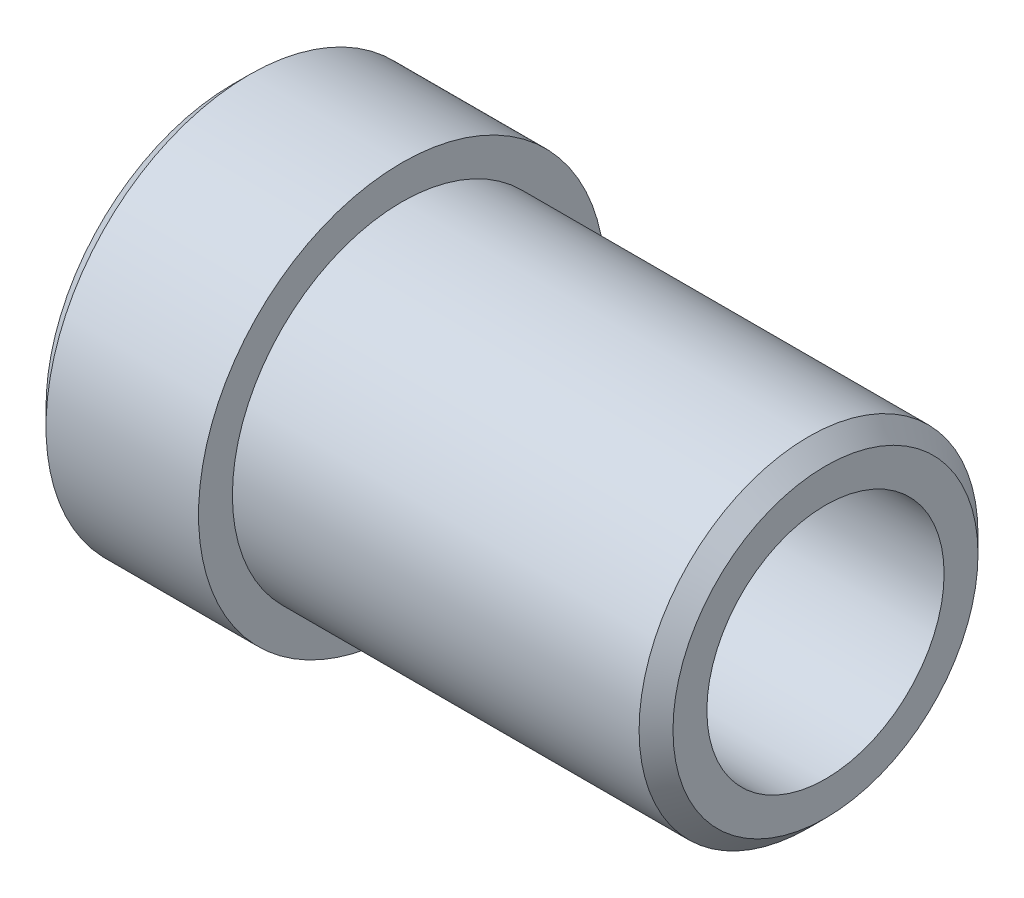
SolidWorks part; units mm, degrees
ref_plane "Front Plane" through (0, 0, 0) normal (0, 0, 1) x (1, 0, 0)
ref_plane "Top Plane" through (0, 0, 0) normal (0, 1, 0) x (1, 0, 0)
ref_plane "Right Plane" through (0, 0, 0) normal (1, 0, 0) x (0, 0, -1)
sketch "Sketch1" plane through (0, 0, 0) normal (0, 0, 1) x (1, 0, 0)
  line L0 (0, 0) -> (-35, 0) construction
  line L1 (0, 0) -> (0, -10)
  line L2 (0, -10) -> (-25, -10)
  line L3 (-25, -10) -> (-25, -12)
  line L4 (-25, -12) -> (-35, -12)
  line L5 (-35, -12) -> (-35, 0)
  line L6 (0, 0) -> (-35, 0)
  dimension "D1" = 10
  dimension "D2" = 10
  dimension "D3" = 12
  dimension "D4" = 35
  dimension "D5" = 2
revolve "Revolve1" add sketch "Sketch1" angle 360 about L0
sketch "Sketch3" plane through (0, 0, 0) normal (1, 0, 0) x (0, 0, -1)
  circle A1 centre (0, 0) radius 7
  dimension "D1" = 14
extrude "Cut-Extrude1" cut sketch "Sketch3" against normal through all
chamfer "Chamfer1" distance 1 angle 45 2 edges at (-35, 12, 0) (0, 10, 0)
